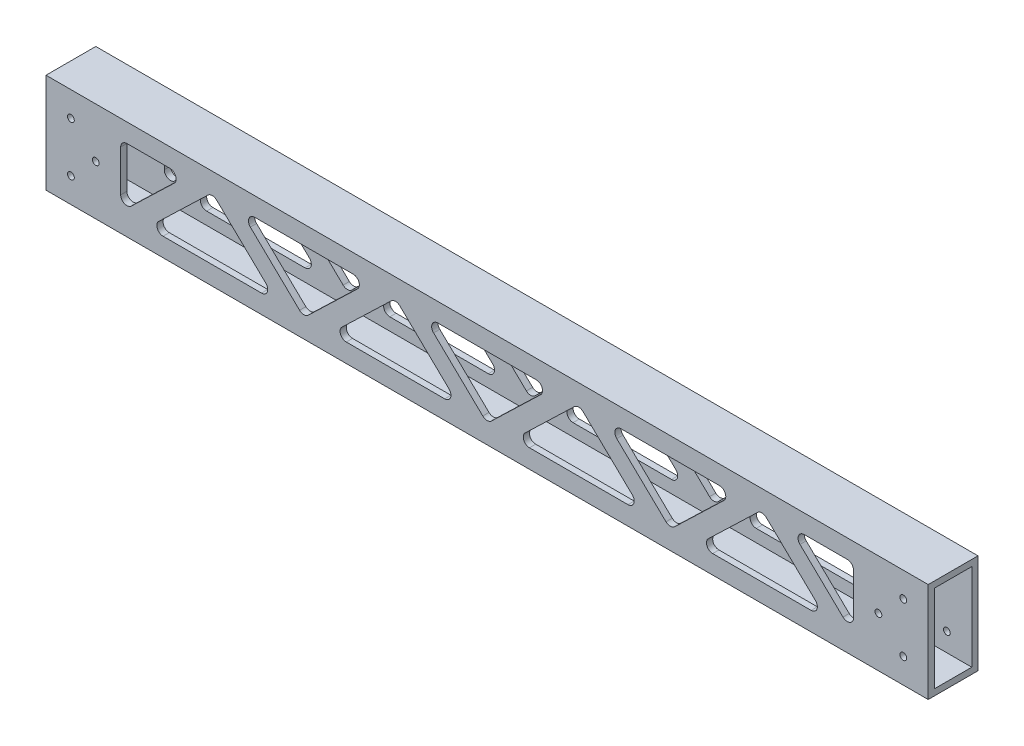
SolidWorks part; units mm, degrees
material "6061-T6 (SS)"
ref_plane "Front Plane" through (0, 0, 0) normal (0, 0, 1) x (1, 0, 0)
ref_plane "Top Plane" through (0, 0, 0) normal (0, 1, 0) x (1, 0, 0)
ref_plane "Right Plane" through (0, 0, 0) normal (1, 0, 0) x (0, 0, -1)
sketch "Sketch1" plane through (0, 0, 0) normal (1, 0, 0) x (0, 0, -1)
  line L0 (9.525, 25.4) -> (9.525, 22.225) construction
  line L1 (-9.525, -22.225) -> (9.525, -22.225)
  line L2 (-9.525, -22.225) -> (-9.525, 22.225)
  line L3 (-9.525, 22.225) -> (9.525, 22.225)
  line L4 (9.525, -22.225) -> (9.525, 22.225)
  line L5 (-9.525, -22.225) -> (9.525, 22.225) construction
  line L6 (-9.525, 22.225) -> (9.525, -22.225) construction
  line L7 (-12.7, -25.4) -> (12.7, -25.4)
  line L8 (-12.7, -25.4) -> (-12.7, 25.4)
  line L9 (-12.7, 25.4) -> (12.7, 25.4)
  line L10 (12.7, -25.4) -> (12.7, 25.4)
  line L11 (-12.7, -25.4) -> (12.7, 25.4) construction
  line L12 (-12.7, 25.4) -> (12.7, -25.4) construction
  line L13 (9.525, 22.225) -> (12.7, 22.225) construction
  point P0 (0, 0)
  point P6 (0, 0)
  dimension "D1" = 50.8
  dimension "D2" = 25.4
  dimension "D3" = 3.175
extrude "Boss-Extrude1" add sketch "Sketch1" along normal mid plane 450.0499
hole_wizard "#8-32 Tapped Hole1" positions "Sketch3" profile "Sketch2" tap size "#8-32" standard "ANSI Inch" end condition through all
sketch "Sketch3" plane through (0, 0, 12.7) normal (0, 0, 1) x (1, 0, 0)
  line L0 (0, 0) -> (0, 50000) construction
  line L1 (0, 0) -> (-50000, 0) construction
  line L2 (-212.3249, -12.7) -> (-212.3249, 49987.3) construction
  line L3 (-225.0249, 25.4) -> (-225.0249, -25.4) construction
  point P0 (-212.3249, 12.7)
  point P2 (-212.3249, -12.7)
  point P4 (-199.6249, 0)
  point P29 (212.3249, 12.7)
  point P30 (199.6249, 0)
  point P31 (212.3249, -12.7)
  dimension "D1" = 25.4
  dimension "D2" = 12.7
  dimension "D3" = 12.7
sketch "Sketch2" plane through (-212.3249, 12.7, 12.7) normal (1, 0, 0) x (0, -1, 0)
  line L0 (0, 0) -> (0, 25.4)
  line L1 (0, 25.4) -> (1.7272, 25.4)
  line L2 (1.7272, 25.4) -> (1.7272, 0)
  line L5 (1.7272, 0) -> (0, 0)
  line L11 (0, -6.35) -> (0, 107.95) construction
  dimension "Thru Tap Drill Dia." = 3.4544
  dimension "Thru Tap Drill Depth" = 25.4
cosmetic thread "Hole Thread1" parameters "D2"=4.1656
cosmetic thread "Hole Thread2" parameters "D2"=4.1656
cosmetic thread "Hole Thread3" parameters "D2"=4.1656
cosmetic thread "Hole Thread4" parameters "D2"=4.1656
cosmetic thread "Hole Thread5" parameters "D2"=4.1656
cosmetic thread "Hole Thread6" parameters "D2"=4.1656
sketch "Sketch4" plane through (0, 0, 12.7) normal (0, 0, 1) x (1, 0, 0)
  line L5 (-186.9249, 15.875) -> (-186.9249, 50015.875) construction
  line L6 (0, 0) -> (0, 50000) construction
  line L7 (186.9249, -4.7854) -> (186.9249, 49995.2146) construction
  line L8 (-225.0249, 25.4) -> (-225.0249, -25.4) construction
  line L9 (215.4999, -15.875) -> (215.4999, 15.875)
  line L10 (-215.4999, -15.875) -> (215.4999, -15.875)
  line L11 (215.4999, 15.875) -> (-215.4999, 15.875)
  line L12 (-215.4999, 15.875) -> (-215.4999, -15.875)
  line L13 (215.4999, -15.875) -> (215.4999, 15.875) construction
  line L14 (-215.4999, -15.875) -> (215.4999, -15.875) construction
  line L15 (215.4999, 15.875) -> (-215.4999, 15.875) construction
  line L16 (-215.4999, 15.875) -> (-215.4999, -15.875) construction
  line L17 (-186.9249, 15.875) -> (-186.9249, -15.875)
  line L18 (-186.9249, -15.875) -> (-153.9306, 15.875)
  line L19 (-153.9306, 15.875) -> (-186.9249, 15.875)
  line L20 (-140.1937, 15.875) -> (-173.1881, -15.875)
  line L21 (-173.1881, -15.875) -> (-107.1994, -15.875)
  line L22 (-107.1994, -15.875) -> (-140.1937, 15.875)
  line L23 (-126.4568, 15.875) -> (-93.4625, -15.875)
  line L24 (-93.4625, -15.875) -> (-60.4681, 15.875)
  line L25 (-60.4681, 15.875) -> (-126.4568, 15.875)
  line L26 (-46.7312, 15.875) -> (-79.7256, -15.875)
  line L27 (-79.7256, -15.875) -> (-13.7369, -15.875)
  line L28 (-13.7369, -15.875) -> (-46.7312, 15.875)
  line L29 (-32.9944, 15.875) -> (0, -15.875)
  line L30 (0, -15.875) -> (32.9944, 15.875)
  line L31 (32.9944, 15.875) -> (-32.9944, 15.875)
  line L32 (13.7369, -15.875) -> (46.7312, 15.875)
  line L33 (46.7312, 15.875) -> (79.7256, -15.875)
  line L34 (79.7256, -15.875) -> (13.7369, -15.875)
  line L35 (60.4681, 15.875) -> (93.4625, -15.875)
  line L36 (93.4625, -15.875) -> (126.4568, 15.875)
  line L37 (126.4568, 15.875) -> (60.4681, 15.875)
  line L38 (107.1994, -15.875) -> (140.1937, 15.875)
  line L39 (140.1937, 15.875) -> (173.1881, -15.875)
  line L40 (173.1881, -15.875) -> (107.1994, -15.875)
  line L41 (186.9249, 15.875) -> (186.9249, -15.875)
  line L42 (186.9249, -15.875) -> (153.9306, 15.875)
  line L43 (153.9306, 15.875) -> (186.9249, 15.875)
  line L44 (-32.9944, 15.875) -> (-60.4681, 15.875) construction
  line L46 (-79.7256, -15.875) -> (-107.1994, -15.875) construction
  line L47 (-153.9306, 15.875) -> (-126.4568, 15.875) construction
  dimension "D2" = 38.1
  dimension "D3" = 9.525
  dimension "D1" = 9.525
extrude "Cut-Extrude1" cut sketch "Sketch4" against normal through all
fillet "Fillet1" radius 3.175 54 edges at (-186.9249, -15.875, -11.1125) (-186.9249, 15.875, -11.1125) (-153.9306, 15.875, -11.1125) (-140.1937, 15.875, -11.1125) (-107.1994, -15.875, -11.1125) (-93.4625, -15.875, -11.1125) (-126.4568, 15.875, -11.1125) (-60.4681, 15.875, -11.1125) (-79.7256, -15.875, -11.1125) (-46.7312, 15.875, -11.1125) (-13.7369, -15.875, -11.1125) (0, -15.875, -11.1125) (-32.9944, 15.875, -11.1125) (32.9944, 15.875, -11.1125) (46.7312, 15.875, -11.1125) (79.7256, -15.875, -11.1125) (13.7369, -15.875, -11.1125) (93.4625, -15.875, -11.1125) (60.4681, 15.875, -11.1125) (126.4568, 15.875, -11.1125) (140.1937, 15.875, -11.1125) (173.1881, -15.875, -11.1125) (107.1994, -15.875, -11.1125) (186.9249, -15.875, -11.1125) (153.9306, 15.875, -11.1125) (186.9249, 15.875, -11.1125) (-173.1881, -15.875, -11.1125) (-153.9306, 15.875, 11.1125) (-186.9249, -15.875, 11.1125) (-186.9249, 15.875, 11.1125) (-107.1994, -15.875, 11.1125) (-140.1937, 15.875, 11.1125) (-60.4681, 15.875, 11.1125) (-93.4625, -15.875, 11.1125) (-126.4568, 15.875, 11.1125) (-13.7369, -15.875, 11.1125) (-79.7256, -15.875, 11.1125) (-46.7312, 15.875, 11.1125) (32.9944, 15.875, 11.1125) (0, -15.875, 11.1125) (-32.9944, 15.875, 11.1125) (13.7369, -15.875, 11.1125) (46.7312, 15.875, 11.1125) (79.7256, -15.875, 11.1125) (126.4568, 15.875, 11.1125) (93.4625, -15.875, 11.1125) (60.4681, 15.875, 11.1125) (107.1994, -15.875, 11.1125) (140.1937, 15.875, 11.1125) (173.1881, -15.875, 11.1125) (186.9249, 15.875, 11.1125) (186.9249, -15.875, 11.1125) (153.9306, 15.875, 11.1125) (-173.1881, -15.875, 11.1125)
